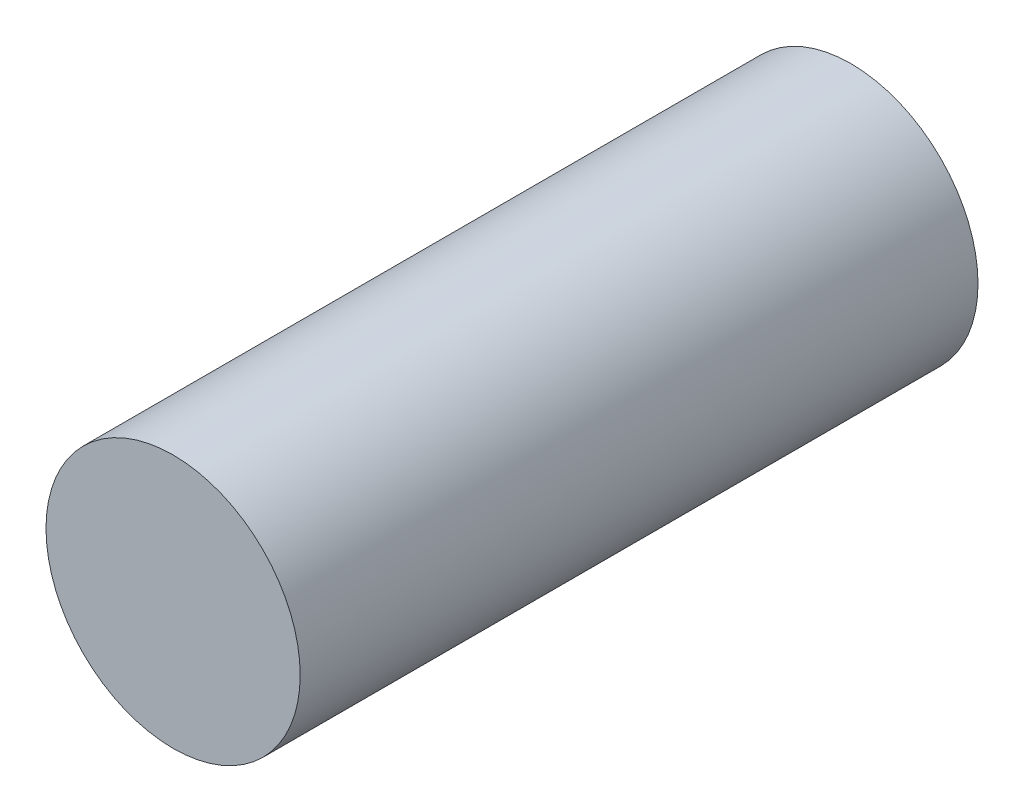
SolidWorks part; units mm, degrees
ref_plane "Front Plane" through (0, 0, 0) normal (0, 0, 1) x (1, 0, 0)
ref_plane "Top Plane" through (0, 0, 0) normal (0, 1, 0) x (1, 0, 0)
ref_plane "Right Plane" through (0, 0, 0) normal (1, 0, 0) x (0, 0, -1)
sketch "Sketch1" plane through (0, 0, 0) normal (0, 0, 1) x (1, 0, 0)
  circle A0 centre (0, 0) radius 76.2
extrude "Boss-Extrude1" add sketch "Sketch1" along normal blind 406.4
